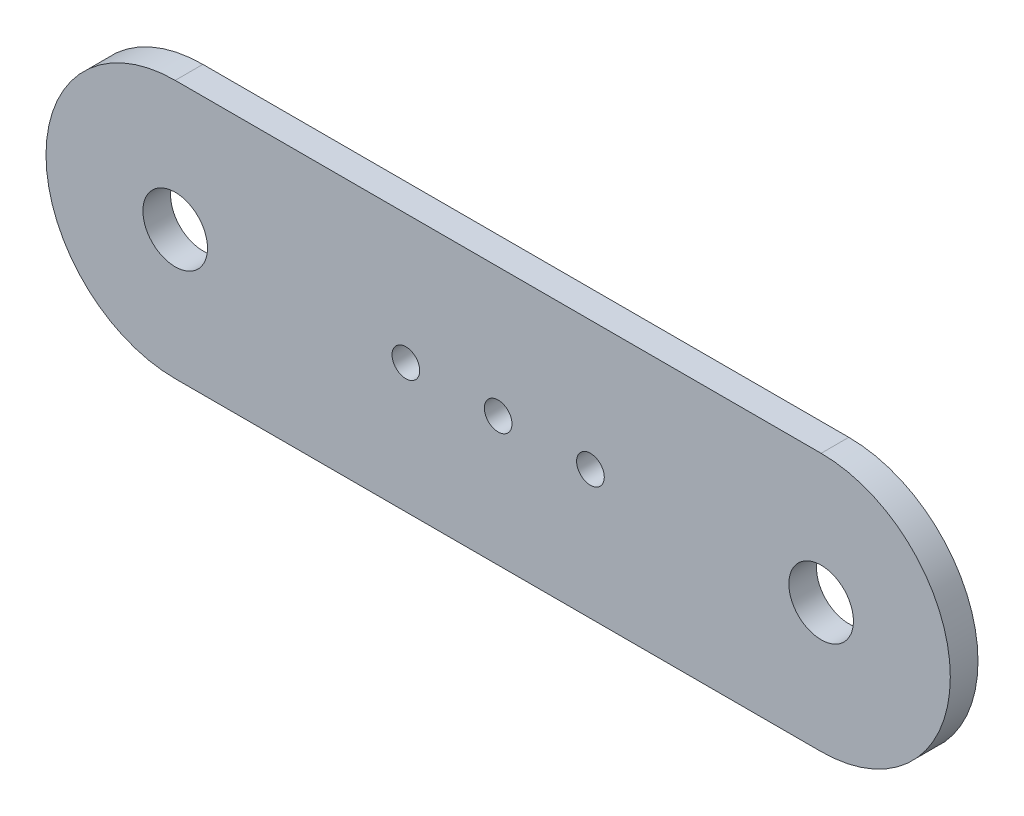
SolidWorks part; units mm, degrees
ref_plane "Front Plane" through (0, 0, 0) normal (0, 0, 1) x (1, 0, 0)
ref_plane "Top Plane" through (0, 0, 0) normal (0, 1, 0) x (1, 0, 0)
ref_plane "Right Plane" through (0, 0, 0) normal (1, 0, 0) x (0, 0, -1)
sketch "Sketch1" plane through (0, 0, 0) normal (0, 0, 1) x (1, 0, 0)
  line L0 (0, 14) -> (70, 14)
  line L1 (0, -14) -> (70, -14)
  line L2 (-1000, 0) -> (49000, 0) construction
  line L3 (35, -1000) -> (35, 49000) construction
  line L4 (25, -1001.1392) -> (25, 48998.8608) construction
  line L5 (45, -1003.2967) -> (45, 48996.7033) construction
  circle A0 centre (25, 0) radius 1.5
  circle A1 centre (0, 0) radius 3.5
  circle A2 centre (35, 0) radius 1.5
  circle A3 centre (45, 0) radius 1.5
  circle A6 centre (70, 0) radius 3.5
  arc A12 (0, 14) -> (0, -14) centre (0, 0) ccw
  arc A13 (70, -14) -> (70, 14) centre (70, 0) ccw
  dimension "D1" = 7
  dimension "D2" = 35
  dimension "D3" = 10
  dimension "D4" = 10
  dimension "D5" = 3
  dimension "D6" = 3
  dimension "D9" = 28
  dimension "D10" = 28
  dimension "D11" = 3
  dimension "D8" = 70
  dimension "D7" = 2
extrude "Boss-Extrude1" add sketch "Sketch1" along normal blind 3
